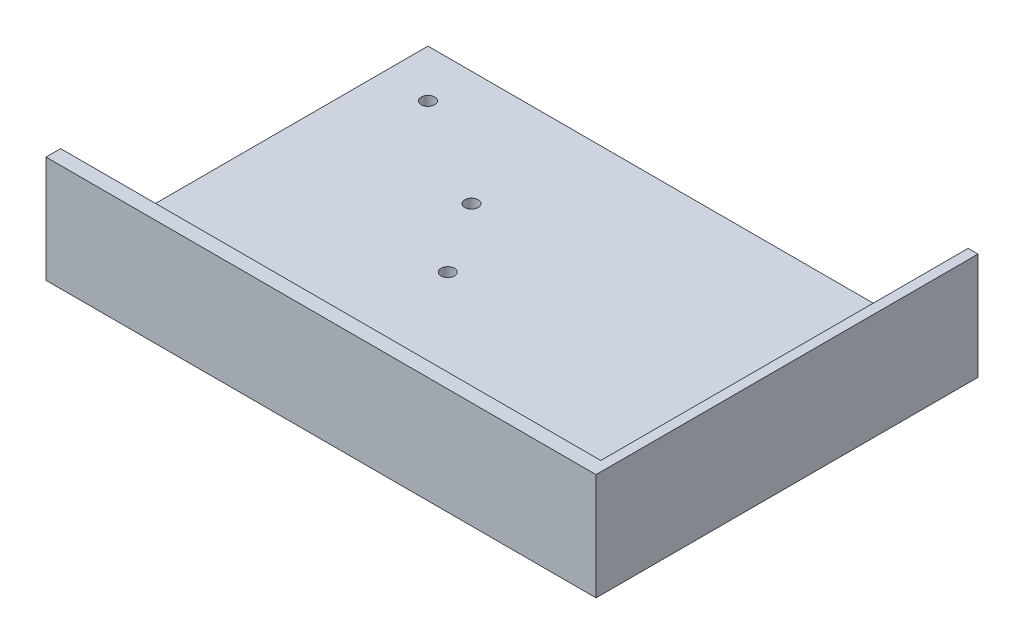
SolidWorks part; units mm, degrees
ref_plane "Front Plane" through (0, 0, 0) normal (0, 0, 1) x (1, 0, 0)
ref_plane "Top Plane" through (0, 0, 0) normal (0, 1, 0) x (1, 0, 0)
ref_plane "Right Plane" through (0, 0, 0) normal (1, 0, 0) x (0, 0, -1)
sketch "Sketch1" plane through (0, 0, 0) normal (0, 1, 0) x (1, 0, 0)
  line L1 (-139.1, -96.6) -> (139.1, -96.6)
  line L2 (-139.1, -96.6) -> (-139.1, 96.6)
  line L3 (-139.1, 96.6) -> (139.1, 96.6)
  line L4 (139.1, -96.6) -> (139.1, 96.6)
  line L5 (-139.1, -96.6) -> (139.1, 96.6) construction
  line L6 (-139.1, 96.6) -> (139.1, -96.6) construction
  point P0 (0, 0)
  dimension "D1" = 278.2
  dimension "D2" = 193.2
extrude "Shell Block" add sketch "Sketch1" along normal blind 27
ref_plane "Shell Front" through (0, 27, 0) normal (0, 1, 0) x (1, 0, 0)
sketch "Sketch2" plane through (0, 27, 0) normal (0, 1, 0) x (1, 0, 0)
  line L1 (-136.6, -92.9) -> (136.6, -92.9)
  line L2 (-136.6, -92.9) -> (-136.6, 92.9)
  line L3 (-136.6, 92.9) -> (136.6, 92.9)
  line L4 (136.6, -92.9) -> (136.6, 92.9)
  line L5 (-136.6, -92.9) -> (136.6, 92.9) construction
  line L6 (-136.6, 92.9) -> (136.6, -92.9) construction
  point P0 (0, 0)
  dimension "D1" = 273.2
  dimension "D2" = 185.8
extrude "Front Opening" cut sketch "Sketch2" against normal blind 1.5
ref_plane "Under Lip" through (0, 25.5, 0) normal (0, 1, 0) x (1, 0, 0)
sketch "Sketch3" plane through (0, 25.5, 0) normal (0, 1, 0) x (1, 0, 0)
  line L1 (-136.6, -94.1) -> (136.6, -94.1)
  line L2 (-136.6, -94.1) -> (-136.6, 94.1)
  line L3 (-136.6, 94.1) -> (136.6, 94.1)
  line L4 (136.6, -94.1) -> (136.6, 94.1)
  line L5 (-136.6, -94.1) -> (136.6, 94.1) construction
  line L6 (-136.6, 94.1) -> (136.6, -94.1) construction
  point P0 (0, 0)
  dimension "D1" = 273.2
  dimension "D2" = 188.2
extrude "Display Pocket" cut sketch "Sketch3" against normal blind 22.5
ref_plane "Back Inner" through (0, 3, 0) normal (0, 1, 0) x (1, 0, 0)
sketch "Sketch4" plane through (0, 3, 0) normal (0, 1, 0) x (1, 0, 0)
  line L1 (-69, 28) -> (-66, 28)
  line L2 (-69, 28) -> (-69, 84)
  line L3 (-69, 84) -> (-66, 84)
  line L4 (-66, 28) -> (-66, 84)
  line L6 (-69, -84) -> (-66, -84)
  line L7 (-69, -84) -> (-69, -28)
  line L8 (-69, -28) -> (-66, -28)
  line L9 (-66, -84) -> (-66, -28)
  line L11 (-77, 28) -> (-74, 28)
  line L12 (-77, 28) -> (-77, 84)
  line L13 (-77, 84) -> (-74, 84)
  line L14 (-74, 28) -> (-74, 84)
  line L16 (-77, -84) -> (-74, -84)
  line L17 (-77, -84) -> (-77, -28)
  line L18 (-77, -28) -> (-74, -28)
  line L19 (-74, -84) -> (-74, -28)
  line L21 (-85, 28) -> (-82, 28)
  line L22 (-85, 28) -> (-85, 84)
  line L23 (-85, 84) -> (-82, 84)
  line L24 (-82, 28) -> (-82, 84)
  line L26 (-85, -84) -> (-82, -84)
  line L27 (-85, -84) -> (-85, -28)
  line L28 (-85, -28) -> (-82, -28)
  line L29 (-82, -84) -> (-82, -28)
  line L31 (-93, 28) -> (-90, 28)
  line L32 (-93, 28) -> (-93, 84)
  line L33 (-93, 84) -> (-90, 84)
  line L34 (-90, 28) -> (-90, 84)
  line L36 (-93, -84) -> (-90, -84)
  line L37 (-93, -84) -> (-93, -28)
  line L38 (-93, -28) -> (-90, -28)
  line L39 (-90, -84) -> (-90, -28)
  line L41 (-101, 28) -> (-98, 28)
  line L42 (-101, 28) -> (-101, 84)
  line L43 (-101, 84) -> (-98, 84)
  line L44 (-98, 28) -> (-98, 84)
  line L46 (-101, -84) -> (-98, -84)
  line L47 (-101, -84) -> (-101, -28)
  line L48 (-101, -28) -> (-98, -28)
  line L49 (-98, -84) -> (-98, -28)
  line L51 (-109, 28) -> (-106, 28)
  line L52 (-109, 28) -> (-109, 84)
  line L53 (-109, 84) -> (-106, 84)
  line L54 (-106, 28) -> (-106, 84)
  line L56 (-109, -84) -> (-106, -84)
  line L57 (-109, -84) -> (-109, -28)
  line L58 (-109, -28) -> (-106, -28)
  line L59 (-106, -84) -> (-106, -28)
  line L61 (-117, 28) -> (-114, 28)
  line L62 (-117, 28) -> (-117, 84)
  line L63 (-117, 84) -> (-114, 84)
  line L64 (-114, 28) -> (-114, 84)
  line L66 (-117, -84) -> (-114, -84)
  line L67 (-117, -84) -> (-117, -28)
  line L68 (-117, -28) -> (-114, -28)
  line L69 (-114, -84) -> (-114, -28)
  line L71 (-125, 28) -> (-122, 28)
  line L72 (-125, 28) -> (-125, 84)
  line L73 (-125, 84) -> (-122, 84)
  line L74 (-122, 28) -> (-122, 84)
  line L76 (-125, -84) -> (-122, -84)
  line L77 (-125, -84) -> (-125, -28)
  line L78 (-125, -28) -> (-122, -28)
  line L79 (-122, -84) -> (-122, -28)
extrude "Vent Slots" cut sketch "Sketch4" against normal blind 4
sketch "Sketch5" plane through (0, 0, 0) normal (1, 0, 0) x (0, 0, -1)
  line L1 (-29, 5) -> (29, 5)
  line L2 (-29, 5) -> (-29, 28)
  line L3 (-29, 28) -> (29, 28)
  line L4 (29, 5) -> (29, 28)
extrude "Cable Exit (-X short side)" cut sketch "Sketch5" against normal blind 140.1
sketch "Sketch6" plane through (0, 3, 0) normal (0, 1, 0) x (1, 0, 0)
  circle A0 centre (-40, -29) radius 1.7
  circle A1 centre (-40, -89) radius 1.7
  circle A2 centre (40, -29) radius 1.7
  circle A3 centre (40, -89) radius 1.7
  circle A4 centre (-52, -47) radius 1.7
  circle A5 centre (-52, -71) radius 1.7
  circle A6 centre (52, -47) radius 1.7
  circle A7 centre (52, -71) radius 1.7
  circle A8 centre (-12, 82) radius 1.7
  circle A9 centre (12, 82) radius 1.7
  circle A10 centre (124, 12) radius 1.7
  circle A11 centre (124, -12) radius 1.7
  circle A12 centre (-12, 12) radius 1.7
  circle A13 centre (-12, -12) radius 1.7
  circle A14 centre (12, 12) radius 1.7
  circle A15 centre (12, -12) radius 1.7
  circle A16 centre (-110, -12) radius 1.7
  circle A17 centre (-110, 12) radius 1.7
  circle A18 centre (-86, -12) radius 1.7
  circle A19 centre (-86, 12) radius 1.7
extrude "Bolt Holes" cut sketch "Sketch6" against normal blind 4
sketch "Sketch7" plane through (0, 0, 0) normal (0, 1, 0) x (1, 0, 0)
  line L1 (-200, -200) -> (0, -200)
  line L2 (-200, -200) -> (-200, 200)
  line L3 (-200, 200) -> (0, 200)
  line L4 (0, -200) -> (0, 200)
extrude "Keep one half (X)" cut sketch "Sketch7" against normal through all and the other way through all
sketch "Sketch8" plane through (0, 0, 0) normal (0, 1, 0) x (1, 0, 0)
  line L1 (-200, 0) -> (200, 0)
  line L2 (-200, 0) -> (-200, 200)
  line L3 (-200, 200) -> (200, 200)
  line L4 (200, 0) -> (200, 200)
extrude "Keep one quarter (Z)" cut sketch "Sketch8" against normal through all and the other way through all
equation "\"DispL\"= 272.0"
equation "\"DispW\"= 187.0"
equation "\"DispT\"= 20.0"
equation "\"Clr\"= 0.6"
equation "\"Wall\"= 2.5"
equation "\"BackT\"= 3.0"
equation "\"CableRoom\"= 4.0"
equation "\"LipW\"= 1.2"
equation "\"LipT\"= 1.5"
equation "\"CableW\"= 58.0"
equation "\"CableH\"= 16.0"
equation "\"BoltD\"= 3.4"
equation "\"ShellL\"= \"DispL\" + 2 * \"Clr\" + 2 * \"Wall\""
equation "\"ShellW\"= \"DispW\" + 2 * \"Clr\" + 2 * \"Wall\""
equation "\"ShellH\"= \"BackT\" + \"DispT\" + \"CableRoom\""
equation "\"D1@Sketch1\" = \"ShellL\""
equation "\"D2@Sketch1\" = \"ShellW\""
equation "\"D1@Shell Block\" = \"ShellH\""
equation "\"D1@Shell Front\" = \"ShellH\""
equation "\"D1@Sketch2\" = \"DispL\" + 2 * \"Clr\""
equation "\"D2@Sketch2\" = \"DispW\" + 2 * \"Clr\" - 2 * \"LipW\""
equation "\"D1@Front Opening\" = \"LipT\""
equation "\"D1@Under Lip\" = \"ShellH\" - \"LipT\""
equation "\"D1@Sketch3\" = \"DispL\" + 2 * \"Clr\""
equation "\"D2@Sketch3\" = \"DispW\" + 2 * \"Clr\""
equation "\"D1@Display Pocket\" = \"ShellH\" - \"LipT\" - \"BackT\""
equation "\"D1@Back Inner\" = \"BackT\""
